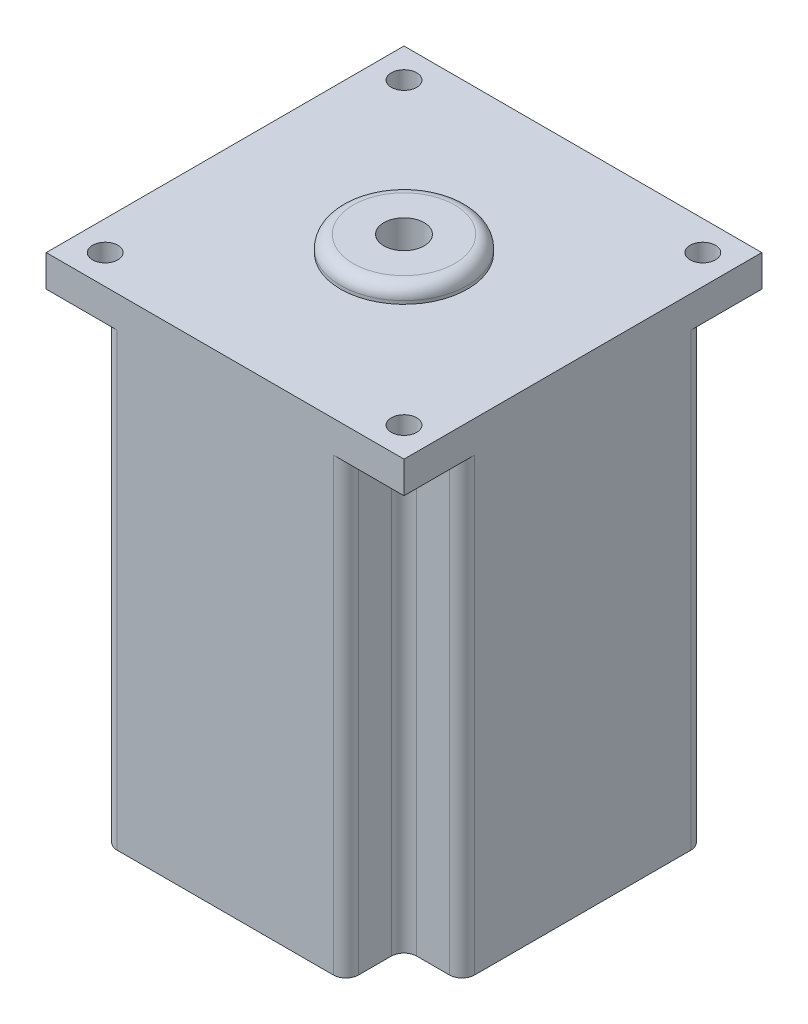
SolidWorks part; units mm, degrees
ref_plane "Front Plane" through (0, 0, 0) normal (0, 0, 1) x (1, 0, 0)
ref_plane "Top Plane" through (0, 0, 0) normal (0, 1, 0) x (1, 0, 0)
ref_plane "Right Plane" through (0, 0, 0) normal (1, 0, 0) x (0, 0, -1)
sketch "Sketch2" plane through (0, 0, 0) normal (0, 1, 0) x (1, 0, 0)
  line L1 (-28.2, 28.2) -> (28.2, 28.2)
  line L2 (-28.2, 28.2) -> (-28.2, -28.2)
  line L3 (-28.2, -28.2) -> (28.2, -28.2)
  line L4 (28.2, 28.2) -> (28.2, -28.2)
  line L5 (-28.2, 28.2) -> (28.2, -28.2) construction
  line L6 (-28.2, -28.2) -> (28.2, 28.2) construction
  point P0 (0, 0)
  dimension "D1" = 56.4
  dimension "D2" = 56.4
extrude "Boss-Extrude1" add sketch "Sketch2" along normal blind 76
sketch "Sketch3" plane through (0, 76, 0) normal (0, 1, 0) x (1, 0, 0)
  line L1 (-23.55, 23.55) -> (23.55, 23.55)
  line L2 (-23.55, 23.55) -> (-23.55, -23.55)
  line L3 (-23.55, -23.55) -> (23.55, -23.55)
  line L4 (23.55, 23.55) -> (23.55, -23.55)
  line L5 (-23.55, 23.55) -> (23.55, -23.55) construction
  line L6 (-23.55, -23.55) -> (23.55, 23.55) construction
  circle A0 centre (-23.55, 23.55) radius 2
  circle A1 centre (23.55, 23.55) radius 2
  circle A2 centre (-23.55, -23.55) radius 2
  circle A3 centre (23.55, -23.55) radius 2
  circle A4 centre (0, 0) radius 3.175
  point P0 (0, 0)
  dimension "D3" = 4
  dimension "D4" = 4
  dimension "D5" = 4
  dimension "D6" = 4
  dimension "D7" = 6.35
  dimension "D1" = 47.1
  dimension "D2" = 47.1
extrude "Cut-Extrude1" cut sketch "Sketch3" against normal blind 76 contours L1 A0 L2 | L2 A0 L1 | L4 A1 L1 | L1 A1 L4 | A4 | L2 A2 L3 | L3 A2 L2 | L4 A3 L3 | L3 A3 L4
sketch "Sketch5" plane through (0, 0, 0) normal (0, -1, 0) x (-1, 0, 0)
  line L0 (19.05, 21.05) -> (19.05, 28.2)
  line L7 (-28.2, 28.2) -> (28.2, 28.2) construction
  line L8 (19.05, 28.2) -> (19.05, 19.05)
  line L9 (28.2, 19.05) -> (21.05, 19.05)
  line L10 (28.2, 28.2) -> (28.2, -28.2) construction
  line L11 (-19.05, 21.05) -> (-19.05, 28.2)
  line L12 (-19.05, 28.2) -> (-19.05, 19.05)
  line L13 (-28.2, 19.05) -> (-21.05, 19.05)
  line L14 (-28.2, -28.2) -> (-28.2, 28.2) construction
  line L15 (-21.05, -19.05) -> (-28.2, -19.05)
  line L16 (-19.05, -21.05) -> (-19.05, -28.2)
  line L17 (28.2, -28.2) -> (-28.2, -28.2) construction
  line L18 (19.05, -28.2) -> (19.05, -21.05)
  line L19 (21.05, -19.05) -> (28.2, -19.05)
  arc A0 (-19.05, 21.05) -> (-21.05, 19.05) centre (-21.05, 21.05) cw
  arc A1 (19.05, 21.05) -> (21.05, 19.05) centre (21.05, 21.05) ccw
  arc A2 (-21.05, -19.05) -> (-19.05, -21.05) centre (-21.05, -21.05) cw
  arc A3 (19.05, -21.05) -> (21.05, -19.05) centre (21.05, -21.05) cw
  point P0 (0, 0)
  point P30 (-19.05, -19.05)
  circle M5 centre (-23.55, -23.55) radius 2
  circle M6 centre (23.55, -23.55) radius 2
  circle M8 centre (-23.55, 23.55) radius 2
  circle M9 centre (23.55, 23.55) radius 2
  line M10 (-28.2, 28.2) -> (-28.2, -28.2)
  line M11 (-28.2, -28.2) -> (28.2, -28.2)
  line M12 (28.2, -28.2) -> (28.2, 28.2)
  line M13 (28.2, 28.2) -> (-28.2, 28.2)
  dimension "D2" = 2
  dimension "D1" = 9.15
  dimension "D3" = 9.15
  dimension "D4" = 9.15
  dimension "D5" = 9.15
  dimension "D6" = 9.15
  dimension "D7" = 9.15
  dimension "D8" = 9.15
  dimension "D9" = 9.15
extrude "Cut-Extrude2" cut sketch "Sketch5" against normal blind 71 contours L19 L18 M6 M11 M12 | L16 L15 M5 M10 M11 | L13 L11 M10 M8 M13 | L9 L0 M12 M13 M9
fillet "Fillet1" radius 2 8 edges at (-28.2, 35.5, -19.05) (-19.05, 35.5, -28.2) (-28.2, 35.5, 19.05) (-19.05, 35.5, 28.2) (19.05, 35.5, 28.2) (28.2, 35.5, 19.05) (19.05, 35.5, -28.2) (28.2, 35.5, -19.05)
sketch "Sketch6" plane through (0, 76, 0) normal (0, 1, 0) x (1, 0, 0)
  circle A0 centre (0, 0) radius 10
  circle A1 centre (0, 0) radius 3.175
  dimension "D1" = 20
  dimension "D2" = 6.35
extrude "Boss-Extrude2" add sketch "Sketch6" along normal blind 2.5
fillet "Fillet2" radius 2 1 edges at (0, 78.5, 10)
